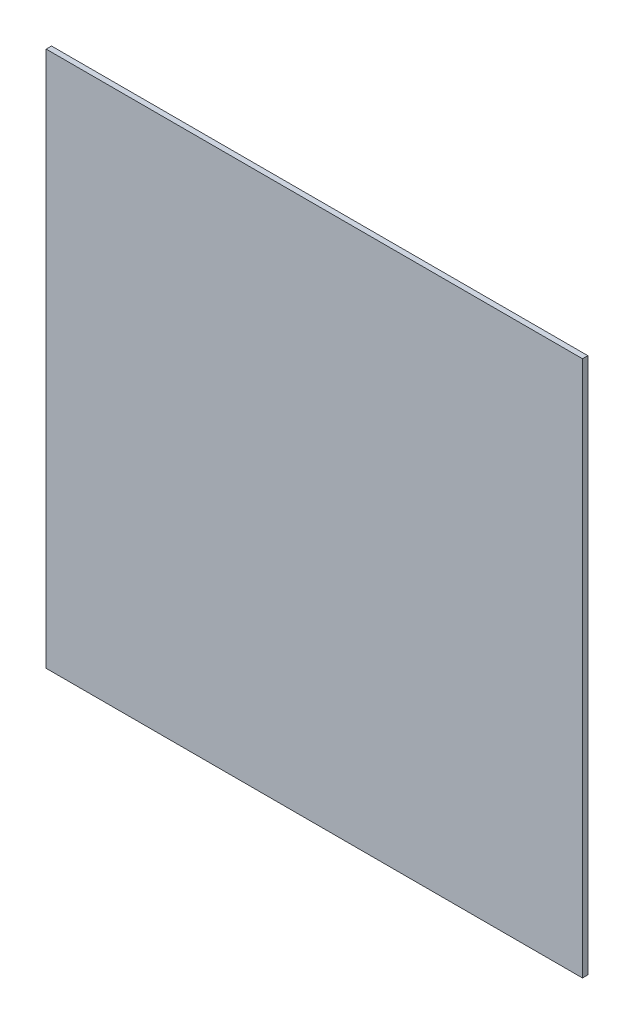
SolidWorks part; units mm, degrees
ref_plane "Front Plane" through (0, 0, 0) normal (0, 0, 1) x (1, 0, 0)
ref_plane "Top Plane" through (0, 0, 0) normal (0, 1, 0) x (1, 0, 0)
ref_plane "Right Plane" through (0, 0, 0) normal (1, 0, 0) x (0, 0, -1)
sketch "Sketch1" plane through (0, 0, 0) normal (0, 0, 1) x (1, 0, 0)
  line L1 (0, 0) -> (400, 0)
  line L2 (0, 0) -> (0, -400)
  line L3 (0, -400) -> (400, -400)
  line L4 (400, 0) -> (400, -400)
  dimension "D1" = 400
  dimension "D2" = 400
extrude "Boss-Extrude1" add sketch "Sketch1" along normal blind 4
